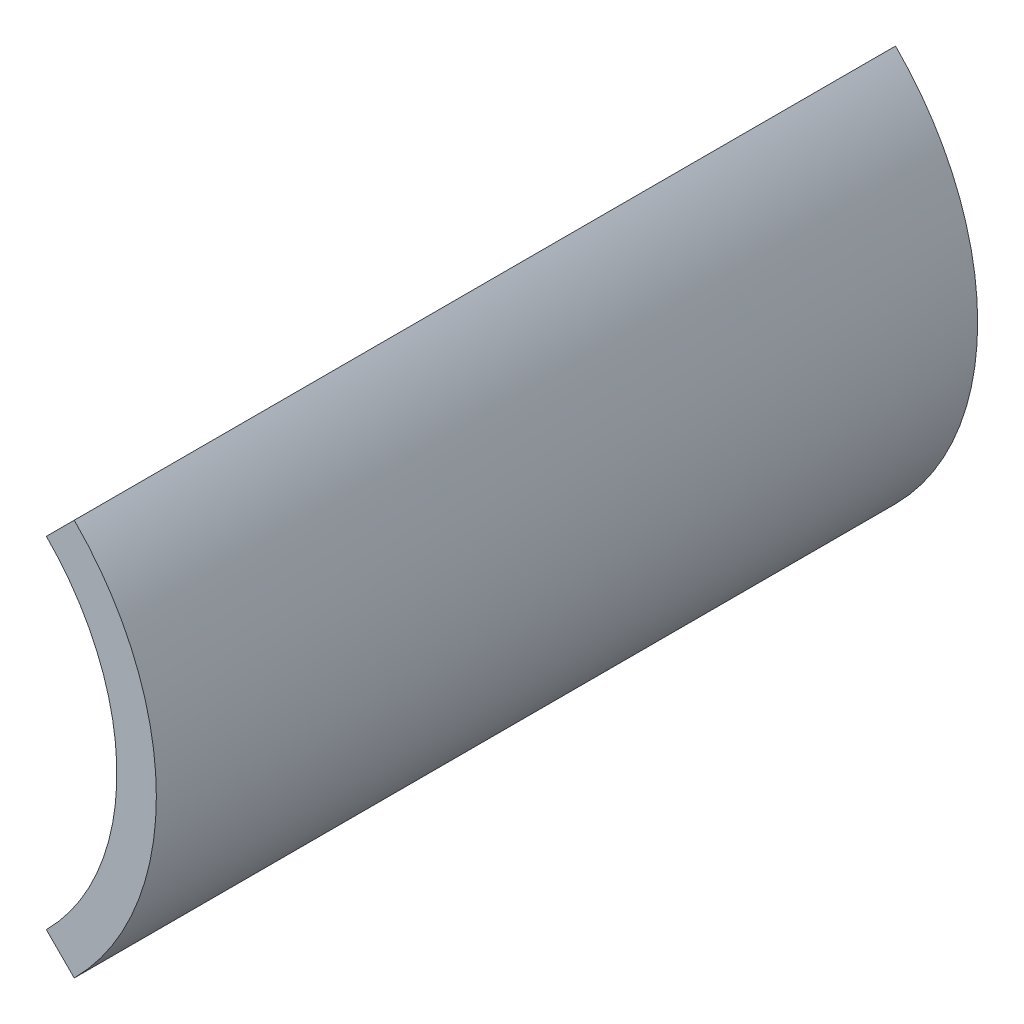
SolidWorks part; units mm, degrees
ref_plane "Front Plane" through (0, 0, 0) normal (0, 0, 1) x (1, 0, 0)
ref_plane "Top Plane" through (0, 0, 0) normal (0, 1, 0) x (1, 0, 0)
ref_plane "Right Plane" through (0, 0, 0) normal (1, 0, 0) x (0, 0, -1)
sketch "Sketch1" plane through (0, 0, 0) normal (0, 0, 1) x (1, 0, 0)
  line L0 (15.25, 0) -> (30.5125, 0) construction
  line L1 (10.7834, 10.7834) -> (12.5511, 12.5511)
  line L2 (10.7834, -10.7834) -> (12.5511, -12.5511)
  arc A0 (12.5511, -12.5511) -> (12.5511, 12.5511) centre (0, 0) ccw
  arc A1 (10.7834, -10.7834) -> (10.7834, 10.7834) centre (0, 0) ccw
  dimension "D1" = 35.5
  dimension "D2" = 30.5
  dimension "D3" = 90
extrude "Boss-Extrude1" add sketch "Sketch1" along normal mid plane 52
